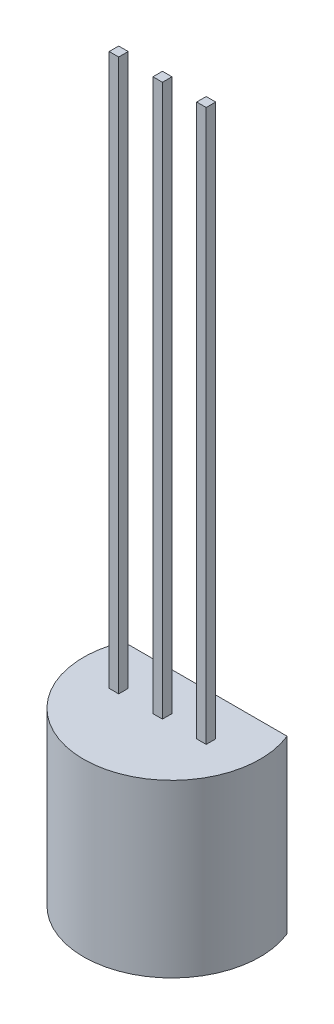
SolidWorks part; units mm, degrees
ref_plane "Front Plane" through (0, 0, 0) normal (0, 0, 1) x (1, 0, 0)
ref_plane "Top Plane" through (0, 0, 0) normal (0, 1, 0) x (1, 0, 0)
ref_plane "Right Plane" through (0, 0, 0) normal (1, 0, 0) x (0, 0, -1)
sketch "Sketch1" plane through (0, 0, 0) normal (0, 1, 0) x (1, 0, 0)
  line L1 (0, 0) -> (4.3, 0)
  arc A0 (0, 0) -> (4.3, 0) centre (2.15, -0.8777) ccw
  dimension "D2" = 4.3
extrude "Boss-Extrude1" add sketch "Sketch1" along normal blind 4.5
sketch "Sketch2" plane through (0, 4.5, 0) normal (0, 1, 0) x (1, 0, 0)
  line L0 (2.15, 0) -> (2.15, -1) construction
  line L1 (4.3, 0) -> (0, 0) construction
  line L2 (3.175, -1) -> (3.425, -1)
  line L3 (2.025, -1) -> (2.275, -1)
  line L4 (2.025, -1) -> (2.025, -1.25)
  line L5 (2.025, -1.25) -> (2.275, -1.25)
  line L6 (2.275, -1) -> (2.275, -1.25)
  line L7 (3.175, -1) -> (3.175, -1.25)
  line L8 (3.175, -1.25) -> (3.425, -1.25)
  line L9 (3.425, -1) -> (3.425, -1.25)
  line L10 (0.875, -1) -> (1.125, -1)
  line L11 (0.875, -1) -> (0.875, -1.25)
  line L12 (0.875, -1.25) -> (1.125, -1.25)
  line L13 (1.125, -1) -> (1.125, -1.25)
  point P9 (2.15, -1)
  point P14 (3.3, -1)
  point P20 (1, -1)
  dimension "D1" = 1
  dimension "D2" = 0.25
  dimension "D3" = 0.25
  dimension "D4" = 2
  dimension "D5" = 2
extrude "Boss-Extrude2" add sketch "Sketch2" along normal blind 14.5
